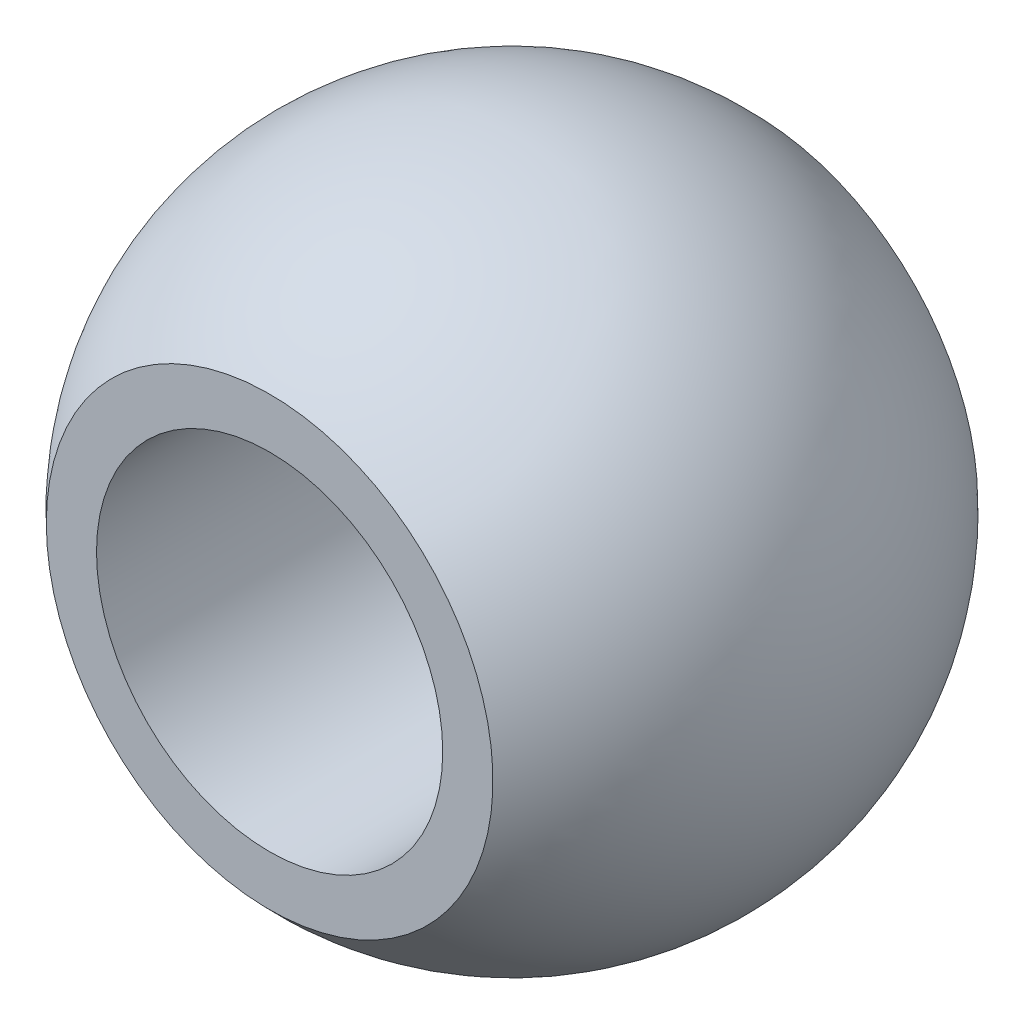
SolidWorks part; units mm, degrees
ref_plane "Front Plane" through (0, 0, 0) normal (0, 0, 1) x (1, 0, 0)
ref_plane "Top Plane" through (0, 0, 0) normal (0, 1, 0) x (1, 0, 0)
ref_plane "Right Plane" through (0, 0, 0) normal (1, 0, 0) x (0, 0, -1)
sketch "Sketch1" plane through (0, 0, 0) normal (0, 0, 1) x (1, 0, 0)
  line L0 (0, -9.5185) -> (0, 9.5185)
  arc A0 (0, -9.5185) -> (0, 9.5185) centre (0, 0) ccw
  point P5 (0, 0)
revolve "Revolve1" add sketch "Sketch1" angle 360 about L0
sketch "Sketch2" plane through (0, 0, 0) normal (0, 0, 1) x (1, 0, 0)
  circle A0 centre (0, 0) radius 5
extrude "Cut-Extrude1" cut sketch "Sketch2" against normal mid plane 35
sketch "Sketch3" plane through (0, 0, 0) normal (0, 1, 0) x (1, 0, 0)
  line L1 (0, 7) -> (11.3334, 7)
  line L2 (11.3334, 7) -> (11.3334, 9.2182)
  line L3 (11.3334, 9.2182) -> (-12.3053, 9.2182)
  line L4 (-12.3053, 9.2182) -> (-12.3053, 7)
  line L5 (-12.3053, 7) -> (0, 7)
  line L6 (0, -7) -> (12.6768, -7)
  line L7 (12.6768, -7) -> (12.6768, -8.961)
  line L8 (12.6768, -8.961) -> (-12.048, -8.961)
  line L9 (-12.048, -8.961) -> (-12.048, -7)
  line L10 (-12.048, -7) -> (0, -7)
extrude "Cut-Extrude2" cut sketch "Sketch3" against normal mid plane 27
sketch "Sketch4" plane through (0, 0, 0) normal (1, 0, 0) x (0, 0, -1)
  point P0 (0, 0)
  point P1 (0, 0)
sketch "Sketch5" plane through (0, 0, 0) normal (1, 0, 0) x (0, 0, -1)
  line L0 (7, -6.45) -> (7, 6.45) construction
  line L1 (-7, 6.45) -> (-7, -6.45) construction
  line L2 (7, -6.45) -> (7, 6.45)
  line L3 (-7, 6.45) -> (-7, -6.45)
  line L4 (-7, 0) -> (7, 0) construction
  line L5 (0, -9.5185) -> (0, 9.5185) construction
  arc A0 (7, 6.45) -> (-7, 6.45) centre (0, 0) ccw construction
  point P13 (0, 0)
